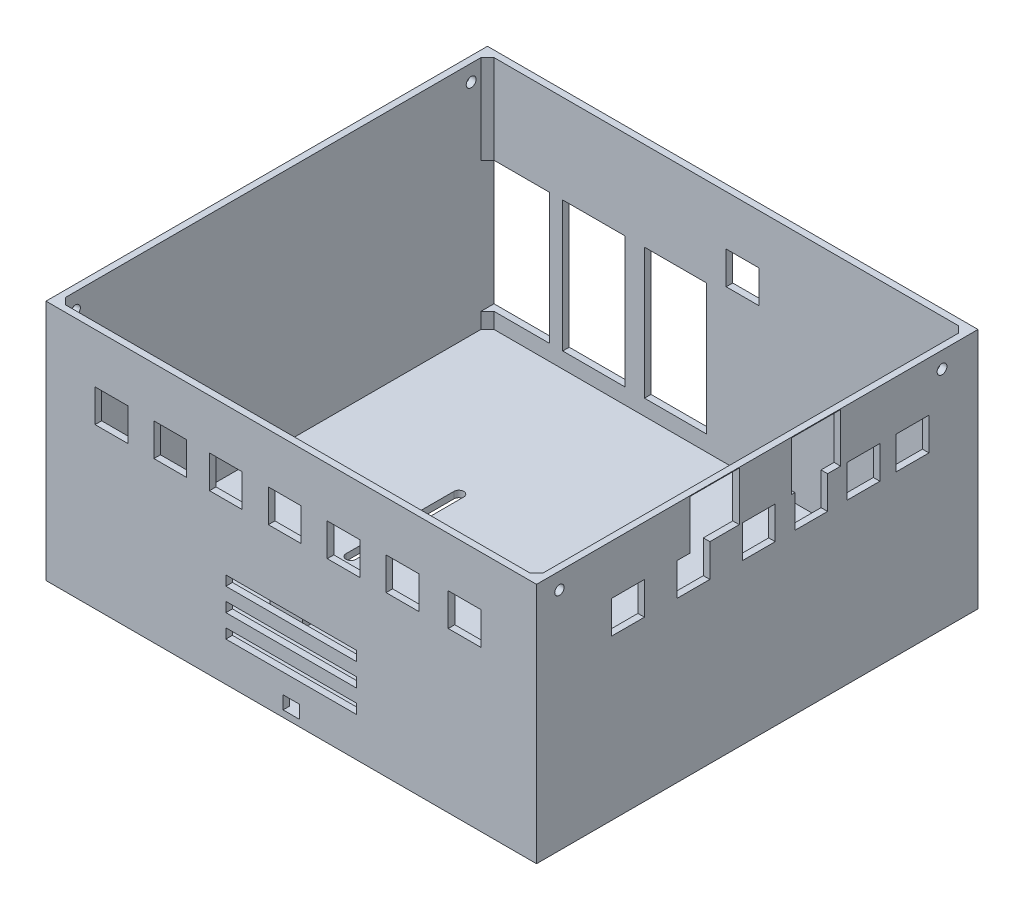
SolidWorks part; units mm, degrees
ref_plane "Alzado" through (0, 0, 0) normal (0, 0, 1) x (1, 0, 0)
ref_plane "Planta" through (0, 0, 0) normal (0, 1, 0) x (1, 0, 0)
ref_plane "Vista lateral" through (0, 0, 0) normal (1, 0, 0) x (0, 0, -1)
sketch "Croquis1" plane through (0, 0, 0) normal (0, 1, 0) x (1, 0, 0)
  line L1 (-75, -67.5) -> (75, -67.5)
  line L2 (-75, -67.5) -> (-75, 67.5)
  line L3 (-75, 67.5) -> (75, 67.5)
  line L4 (75, -67.5) -> (75, 67.5)
  line L5 (-75, -67.5) -> (75, 67.5) construction
  line L6 (-75, 67.5) -> (75, -67.5) construction
  point P0 (0, 0)
  dimension "D1" = 150
  dimension "D2" = 135
extrude "Saliente-Extruir1" add sketch "Croquis1" along normal blind 2
sketch "Croquis2" plane through (0, 2, 0) normal (0, 1, 0) x (1, 0, 0)
  line L0 (31.25, 16.5) -> (31.25, 1.5)
  line L1 (34.25, 1.5) -> (34.25, 16.5)
  line L2 (49.25, 1.5) -> (34.25, 1.5)
  line L3 (34.25, -1.5) -> (49.25, -1.5)
  line L4 (-75, -67.5) -> (75, -67.5) construction
  line L5 (75, -67.5) -> (75, 67.5) construction
  line L6 (-75, 67.5) -> (-75, -67.5) construction
  line L7 (75, 67.5) -> (-75, 67.5) construction
  line L8 (73, -65.5) -> (73, 65.5)
  line L9 (73, 65.5) -> (-73, 65.5)
  line L10 (-73, 65.5) -> (-73, -65.5)
  line L11 (-73, -65.5) -> (73, -65.5)
  line L12 (73, -65.5) -> (73, 65.5) construction
  line L13 (73, 65.5) -> (-73, 65.5) construction
  line L14 (-73, 65.5) -> (-73, -65.5) construction
  line L15 (-73, -65.5) -> (73, -65.5) construction
  line L16 (-75, -67.5) -> (75, -67.5)
  line L17 (75, -67.5) -> (75, 67.5)
  line L18 (-75, 67.5) -> (-75, -67.5)
  line L19 (75, 67.5) -> (-75, 67.5)
  line L21 (-73, 0) -> (73, 0) construction
  line L42 (-73, 65.5) -> (73, 65.5)
  line L43 (73, -65.5) -> (-73, -65.5)
  line L44 (34.25, -16.5) -> (34.25, -1.5)
  line L45 (31.25, -1.5) -> (31.25, -16.5)
  line L46 (16.25, -1.5) -> (31.25, -1.5)
  line L47 (31.25, 1.5) -> (16.25, 1.5)
  line L56 (-31.25, -16.5) -> (-31.25, -1.5)
  line L57 (-34.25, -1.5) -> (-34.25, -16.5)
  line L58 (-49.25, -1.5) -> (-34.25, -1.5)
  line L59 (-34.25, 1.5) -> (-49.25, 1.5)
  line L60 (-34.25, 16.5) -> (-34.25, 1.5)
  line L61 (-31.25, 1.5) -> (-31.25, 16.5)
  line L62 (-16.25, 1.5) -> (-31.25, 1.5)
  line L63 (-31.25, -1.5) -> (-16.25, -1.5)
  line L64 (0, 14.75) -> (0, -8.44) construction
  circle A8 centre (0, 0) radius 8.44
  arc A9 (31.25, 16.5) -> (34.25, 16.5) centre (32.75, 16.5) cw
  arc A10 (49.25, 1.5) -> (49.25, -1.5) centre (49.25, 0) cw
  arc A11 (16.25, 1.5) -> (16.25, -1.5) centre (16.25, 0) ccw
  circle A12 centre (0, 0) radius 8.44
  arc A13 (34.25, -16.5) -> (31.25, -16.5) centre (32.75, -16.5) cw
  circle A17 centre (0, 0) radius 8.44
  arc A19 (-31.25, -16.5) -> (-34.25, -16.5) centre (-32.75, -16.5) cw
  arc A20 (-49.25, -1.5) -> (-49.25, 1.5) centre (-49.25, 0) cw
  arc A21 (-16.25, -1.5) -> (-16.25, 1.5) centre (-16.25, 0) ccw
  circle A22 centre (0, 0) radius 8.44
  arc A23 (-34.25, 16.5) -> (-31.25, 16.5) centre (-32.75, 16.5) cw
  point P101 (0, 0)
  dimension "D1" = 2
  dimension "D13" = 4
extrude "Cortar-Extruir2" cut sketch "Croquis2" against normal blind 2 contours L60 L59 A20 L58 L57 A19 L56 L63 A21 L62 L61 A23 | L44 L3 A10 L2 L1 A9 L0 L47 A11 L46 L45 A13
sketch "Croquis4" plane through (0, 2, 0) normal (0, 1, 0) x (1, 0, 0)
  line L10 (-75, -67.5) -> (75, -67.5) construction
  line L11 (75, -67.5) -> (75, 67.5) construction
  line L12 (75, 67.5) -> (-75, 67.5) construction
  line L13 (-75, 67.5) -> (-75, -67.5) construction
  line L14 (-73, -65.5) -> (73, -65.5)
  line L15 (73, -65.5) -> (73, 65.5)
  line L16 (-73, 65.5) -> (-73, -65.5)
  line L17 (73, 65.5) -> (-73, 65.5)
  line L18 (-73, -65.5) -> (73, -65.5)
  line L19 (73, -65.5) -> (73, 65.5)
  line L20 (-73, 65.5) -> (-73, -65.5)
  line L21 (73, 65.5) -> (-73, 65.5)
  line L22 (-75, -67.5) -> (75, -67.5)
  line L23 (75, -67.5) -> (75, 67.5)
  line L24 (75, 67.5) -> (-75, 67.5)
  line L25 (-75, 67.5) -> (-75, -67.5)
  dimension "D1" = 2
extrude "Saliente-Extruir3" add sketch "Croquis4" along normal blind 72
sketch "Croquis5" plane through (-75, 0, 0) normal (-1, 0, 0) x (0, 0, 1)
  line L0 (-67.5, 74) -> (67.5, 74) construction
  line L1 (-65.5, 72) -> (-40.9426, 72) construction
  line L2 (-65.5, 72) -> (-65.5, 39.0856) construction
  line L5 (-67.5, 74) -> (-67.5, 0) construction
  circle A0 centre (-60.5, 69) radius 1.5
  dimension "D5" = 3
  dimension "D1" = 2
  dimension "D2" = 2
  dimension "D3" = 5
  dimension "D4" = 5
extrude "Cortar-Extruir3" cut sketch "Croquis5" against normal blind 2
sketch "Croquis6" plane through (-75, 0, 0) normal (-1, 0, 0) x (0, 0, 1)
  line L0 (42.5638, 72) -> (65.5, 72) construction
  line L1 (65.5, 72) -> (65.5, 36.9211) construction
  line L2 (-67.5, 74) -> (67.5, 74) construction
  line L3 (67.5, 74) -> (67.5, 0) construction
  circle A0 centre (60.5, 69) radius 1.5
  dimension "D3" = 3
  dimension "D1" = 2
  dimension "D2" = 2
  dimension "D4" = 5
  dimension "D5" = 5
extrude "Cortar-Extruir4" cut sketch "Croquis6" against normal blind 2
sketch "Croquis7" plane through (75, 0, 0) normal (1, 0, 0) x (0, 0, -1)
  line L0 (61.5, 43.6399) -> (61.5, 72) construction
  line L1 (61.5, 72) -> (54.1468, 72) construction
  line L2 (-67.5, 74) -> (67.5, 74) construction
  line L3 (67.5, 74) -> (67.5, 0) construction
  circle A0 centre (56.5, 69) radius 1.5
  dimension "D3" = 3
  dimension "D1" = 2
  dimension "D2" = 6
  dimension "D4" = 5
  dimension "D5" = 5
extrude "Cortar-Extruir5" cut sketch "Croquis7" against normal blind 2
sketch "Croquis8" plane through (75, 0, 0) normal (1, 0, 0) x (0, 0, -1)
  line L0 (-54.2689, 72) -> (-65.5, 72) construction
  line L1 (-65.5, 72) -> (-65.5, 42.9466) construction
  line L2 (-67.5, 74) -> (67.5, 74) construction
  line L3 (-67.5, 74) -> (-67.5, 0) construction
  circle A0 centre (-60.5, 69) radius 1.4318
  dimension "D1" = 2
  dimension "D2" = 2
  dimension "D3" = 3
  dimension "D4" = 5
extrude "Cortar-Extruir6" cut sketch "Croquis8" against normal blind 2
sketch "Croquis9" plane through (0, 0, 67.5) normal (0, 0, 1) x (1, 0, 0)
  line L0 (75, 58.8) -> (-75, 58.8) construction
  line L1 (75, 74) -> (75, 0) construction
  line L2 (-75, 74) -> (-75, 0) construction
  line L3 (-75, 74) -> (75, 74) construction
  line L4 (3, 48.8) -> (-7, 48.8)
  line L5 (-50, 58.8) -> (-60, 58.8)
  line L6 (-50, 58.8) -> (-50, 48.8)
  line L7 (-50, 48.8) -> (-60, 48.8)
  line L8 (-60, 58.8) -> (-60, 48.8)
  line L9 (-42, 58.8) -> (-32, 58.8)
  line L10 (-42, 58.8) -> (-42, 48.8)
  line L11 (-42, 48.8) -> (-32, 48.8)
  line L12 (-32, 58.8) -> (-32, 48.8)
  line L13 (-25, 58.8) -> (-15, 58.8)
  line L14 (-25, 58.8) -> (-25, 48.8)
  line L15 (-25, 48.8) -> (-15, 48.8)
  line L16 (-15, 58.8) -> (-15, 48.8)
  line L20 (3, 58.8) -> (3, 48.8)
  line L21 (11, 58.8) -> (21, 58.8)
  line L22 (11, 58.8) -> (11, 48.8)
  line L23 (11, 48.8) -> (21, 48.8)
  line L24 (21, 58.8) -> (21, 48.8)
  line L25 (29, 58.8) -> (39, 58.8)
  line L26 (29, 58.8) -> (29, 48.8)
  line L27 (29, 48.8) -> (39, 48.8)
  line L28 (39, 58.8) -> (39, 48.8)
  line L29 (48, 58.8) -> (58, 58.8)
  line L30 (48, 58.8) -> (48, 48.8)
  line L31 (48, 48.8) -> (58, 48.8)
  line L32 (58, 58.8) -> (58, 48.8)
  line L33 (-7, 48.8) -> (-7, 58.8)
  line L34 (-7, 58.8) -> (3, 58.8)
  dimension "D1" = 15.2
  dimension "D2" = 15
  dimension "D3" = 10
  dimension "D4" = 10
  dimension "D5" = 43
  dimension "D6" = 10
  dimension "D7" = 10
  dimension "D8" = 60
  dimension "D9" = 10
  dimension "D10" = 10
  dimension "D11" = 8
  dimension "D12" = 10
  dimension "D13" = 8
  dimension "D14" = 10
  dimension "D15" = 10
  dimension "D16" = 8
  dimension "D17" = 10
  dimension "D18" = 10
  dimension "D19" = 9
  dimension "D20" = 10
  dimension "D21" = 10
extrude "Cortar-Extruir7" cut sketch "Croquis9" against normal blind 2
sketch "Croquis10" plane through (75, 0, 0) normal (1, 0, 0) x (0, 0, -1)
  line L0 (67.5, 58.8) -> (-67.5, 58.8) construction
  line L1 (67.5, 74) -> (67.5, 0) construction
  line L2 (-67.5, 74) -> (-67.5, 0) construction
  line L3 (-67.5, 74) -> (67.5, 74) construction
  line L4 (11.5, 48.8) -> (11.5, 58.8)
  line L5 (-44.5, 58.8) -> (-34.5, 58.8)
  line L6 (-44.5, 58.8) -> (-44.5, 48.8)
  line L7 (-44.5, 48.8) -> (-34.5, 48.8)
  line L8 (-34.5, 58.8) -> (-34.5, 48.8)
  line L9 (-24.5, 58.8) -> (-14.5, 58.8)
  line L10 (-24.5, 58.8) -> (-24.5, 48.8)
  line L11 (-24.5, 48.8) -> (-14.5, 48.8)
  line L12 (-14.5, 58.8) -> (-14.5, 48.8)
  line L13 (-4.5, 58.8) -> (5.5, 58.8)
  line L14 (-4.5, 58.8) -> (-4.5, 48.8)
  line L15 (-4.5, 48.8) -> (5.5, 48.8)
  line L16 (5.5, 58.8) -> (5.5, 48.8)
  line L19 (11.5, 48.8) -> (21.5, 48.8)
  line L20 (21.5, 58.8) -> (21.5, 48.8)
  line L21 (27.5, 58.8) -> (37.5, 58.8)
  line L22 (27.5, 58.8) -> (27.5, 48.8)
  line L23 (27.5, 48.8) -> (37.5, 48.8)
  line L24 (37.5, 58.8) -> (37.5, 48.8)
  line L25 (42.5, 58.8) -> (52.5, 58.8)
  line L26 (42.5, 58.8) -> (42.5, 48.8)
  line L27 (42.5, 48.8) -> (52.5, 48.8)
  line L28 (52.5, 58.8) -> (52.5, 48.8)
  line L29 (21.5, 58.8) -> (11.5, 58.8)
  point P32 (32.5, 48.8)
  dimension "D1" = 15.2
  dimension "D2" = 10
  dimension "D3" = 10
  dimension "D4" = 10
  dimension "D5" = 10
  dimension "D6" = 10
  dimension "D7" = 10
  dimension "D8" = 10
  dimension "D9" = 10
  dimension "D10" = 10
  dimension "D11" = 10
  dimension "D12" = 10
  dimension "D13" = 10
  dimension "D14" = 23
  dimension "D15" = 53
  dimension "D16" = 73
  dimension "D17" = 6
  dimension "D18" = 15.2
  dimension "D19" = 15
  dimension "D20" = 6
extrude "Cortar-Extruir8" cut sketch "Croquis10" against normal blind 2
sketch "Croquis11" plane through (0, 0, -67.5) normal (0, 0, -1) x (-1, 0, 0)
  line L0 (75, 58.8) -> (-75, 58.8) construction
  line L1 (75, 74) -> (75, 0) construction
  line L2 (-75, 74) -> (-75, 0) construction
  line L3 (-75, 74) -> (75, 74) construction
  line L4 (-73, 58.8) -> (-73, 9.9054) construction
  line L6 (0, 48.8) -> (-10, 48.8)
  line L7 (0, 48.8) -> (0, 58.8)
  line L8 (0, 58.8) -> (-10, 58.8)
  line L9 (-10, 48.8) -> (-10, 58.8)
  line L10 (25, 6.8) -> (6, 6.8)
  line L11 (25, 6.8) -> (25, 46.8)
  line L12 (25, 46.8) -> (6, 46.8)
  line L13 (6, 6.8) -> (6, 46.8)
  line L15 (31, 6.8) -> (50, 6.8)
  line L16 (31, 6.8) -> (31, 46.8)
  line L17 (31, 46.8) -> (50, 46.8)
  line L18 (50, 6.8) -> (50, 46.8)
  line L19 (54, 6.8) -> (73, 6.8)
  line L20 (54, 6.8) -> (54, 46.8)
  line L21 (54, 46.8) -> (73, 46.8)
  line L22 (73, 6.8) -> (73, 46.8)
  dimension "D1" = 15.2
  dimension "D2" = 2
  dimension "D3" = 10
  dimension "D4" = 10
  dimension "D5" = 73
  dimension "D6" = 16
  dimension "D7" = 19
  dimension "D8" = 12
  dimension "D9" = 40
  dimension "D10" = 6
  dimension "D11" = 19
  dimension "D12" = 40
  dimension "D13" = 12
  dimension "D14" = 12
  dimension "D15" = 4
  dimension "D16" = 40
  dimension "D17" = 19
extrude "Cortar-Extruir9" cut sketch "Croquis11" against normal blind 2
sketch "Croquis12" plane through (75, 0, 0) normal (1, 0, 0) x (0, 0, -1)
  line L0 (25.5, 0) -> (25.5, 30.8414) construction
  line L1 (-67.5, 0) -> (67.5, 0) construction
  line L2 (67.5, 74) -> (67.5, 0) construction
  line L3 (10.5, 0) -> (10.5, 30.8414) construction
  line L5 (25.5, 58.8) -> (10.5, 58.8)
  line L6 (25.5, 58.8) -> (25.5, 73.8)
  line L7 (25.5, 73.8) -> (10.5, 73.8)
  line L8 (10.5, 58.8) -> (10.5, 73.8)
  line L9 (-20.5, 0) -> (-20.5, 33.6091) construction
  line L10 (-67.5, 74) -> (-67.5, 0) construction
  line L11 (-67.5, 74) -> (67.5, 74) construction
  line L12 (-20.5, 58.8) -> (-5.5, 58.8)
  line L13 (-20.5, 58.8) -> (-20.5, 73.8)
  line L14 (-20.5, 73.8) -> (-5.5, 73.8)
  line L15 (-5.5, 58.8) -> (-5.5, 73.8)
  dimension "D1" = 42
  dimension "D2" = 15
  dimension "D3" = 15
  dimension "D4" = 15.2
  dimension "D5" = 47
  dimension "D6" = 15.2
  dimension "D7" = 15
  dimension "D8" = 15
sketch "Croquis13" plane through (0, 0, 0) normal (0, -1, 0) x (1, 0, 0)
  line L0 (75, 55.5) -> (-75, 55.5) construction
  line L1 (75, 67.5) -> (75, -67.5) construction
  line L2 (-75, -67.5) -> (-75, 67.5) construction
  line L3 (-75, 67.5) -> (75, 67.5) construction
  line L4 (0, -67.5) -> (0, 67.5) construction
  line L5 (21.5, 55.5) -> (-21.5, 55.5) construction
  line L6 (21.5, 55.5) -> (21.5, 20.5) construction
  line L7 (21.5, 20.5) -> (-21.5, 20.5) construction
  line L8 (-21.5, 55.5) -> (-21.5, 20.5) construction
  line L9 (75, -67.5) -> (-75, -67.5) construction
  line L10 (21.5, 38) -> (-21.5, 38) construction
  line L11 (-21.5, 38) -> (-31.7475, 38) construction
  line L12 (21.5, 47) -> (-21.5, 47) construction
  line L13 (21.5, 47) -> (21.5, 29) construction
  line L14 (21.5, 29) -> (-21.5, 29) construction
  line L15 (-21.5, 47) -> (-21.5, 29) construction
  line L16 (21.5, 47) -> (-21.5, 29) construction
  line L17 (21.5, 29) -> (-21.5, 47) construction
  line L20 (-30.5, 38) -> (-21.5, 38)
  line L21 (30.5, 38) -> (21.5, 38)
  arc A2 (-21.5, 47) -> (-21.5, 29) centre (-21.5, 38) ccw construction
  circle A3 centre (-26, 38) radius 2
  circle A4 centre (26, 38) radius 2
  arc A5 (21.5, 47) -> (21.5, 29) centre (21.5, 38) cw construction
  point P18 (0, 38)
  point P24 (-26.6237, 38)
  dimension "D6" = 4
  dimension "D1" = 12
  dimension "D2" = 35
  dimension "D3" = 21.5
  dimension "D5" = 9
extrude "Cortar-Extruir11" cut sketch "Croquis13" against normal blind 2 contours A3 | A4
sketch "Croquis14" plane through (0, 2, 0) normal (0, 1, 0) x (1, 0, 0)
  line L1 (31, -33) -> (21, -33)
  line L2 (31, -33) -> (31, -43)
  line L3 (31, -43) -> (21, -43)
  line L4 (21, -33) -> (21, -43)
  line L5 (31, -33) -> (21, -43) construction
  line L6 (31, -43) -> (21, -33) construction
  line L7 (-21, -33) -> (-31, -33)
  line L8 (-21, -33) -> (-21, -43)
  line L9 (-21, -43) -> (-31, -43)
  line L10 (-31, -33) -> (-31, -43)
  line L11 (-21, -33) -> (-31, -43) construction
  line L12 (-21, -43) -> (-31, -33) construction
  circle A0 centre (-26, -38) radius 2 construction
  circle A1 centre (26, -38) radius 2 construction
  circle A2 centre (-26, -38) radius 2
  circle A3 centre (26, -38) radius 2
  point P0 (26, -38)
  point P6 (-26, -38)
  dimension "D1" = 10
  dimension "D2" = 10
  dimension "D3" = 10
  dimension "D4" = 10
extrude "Saliente-Extruir4" add sketch "Croquis14" along normal blind 5
sketch "Croquis15" plane through (0, 0, 67.5) normal (0, 0, 1) x (1, 0, 0)
  line L0 (0, 0) -> (0, 74) construction
  line L1 (-75, 0) -> (75, 0) construction
  line L2 (-75, 74) -> (75, 74) construction
  line L4 (2.5, 2) -> (-2.5, 2)
  line L5 (2.5, 2) -> (2.5, 6)
  line L6 (2.5, 6) -> (-2.5, 6)
  line L7 (-2.5, 2) -> (-2.5, 6)
  line L8 (20, 15) -> (-20, 15)
  line L9 (20, 15) -> (20, 12)
  line L10 (20, 12) -> (-20, 12)
  line L11 (-20, 15) -> (-20, 12)
  line L12 (-20, 22) -> (20, 22)
  line L13 (-20, 22) -> (-20, 19)
  line L14 (-20, 19) -> (20, 19)
  line L15 (20, 22) -> (20, 19)
  line L16 (-20, 29) -> (20, 29)
  line L17 (-20, 29) -> (-20, 26)
  line L18 (-20, 26) -> (20, 26)
  line L19 (20, 29) -> (20, 26)
  dimension "D1" = 2
  dimension "D2" = 4
  dimension "D3" = 2.5
  dimension "D4" = 5
  dimension "D5" = 20
  dimension "D6" = 40
  dimension "D7" = 3
  dimension "D8" = 10
  dimension "D9" = 4
  dimension "D10" = 4
  dimension "D11" = 20
  dimension "D12" = 20
  dimension "D13" = 40
  dimension "D14" = 40
  dimension "D15" = 3
  dimension "D16" = 3
extrude "Cortar-Extruir12" cut sketch "Croquis15" against normal blind 2
extrude "Cortar-Extruir13" cut sketch "Croquis12" against normal blind 2
sketch "Croquis16" plane through (0, 74, 0) normal (0, 1, 0) x (1, 0, 0)
  line L0 (-73, -65.5) -> (-73, -63.5)
  line L1 (-73, 65.5) -> (-73, -65.5) construction
  line L2 (-73, -63.5) -> (-71, -65.5)
  line L3 (-73, -65.5) -> (73, -65.5) construction
  line L4 (-71, -65.5) -> (-73, -65.5)
  line L5 (73, -65.5) -> (71, -65.5)
  line L6 (71, -65.5) -> (73, -63.5)
  line L7 (73, -63.5) -> (73, -65.5)
  line L8 (73, 65.5) -> (73, 63.5)
  line L9 (73, -65.5) -> (73, 65.5) construction
  line L10 (73, 63.5) -> (71, 65.5)
  line L11 (73, 65.5) -> (-73, 65.5) construction
  line L12 (71, 65.5) -> (73, 65.5)
  dimension "D1" = 2
  dimension "D2" = 2
  dimension "D3" = 2
  dimension "D4" = 2
  dimension "D5" = 2
  dimension "D6" = 2
extrude "Saliente-Extruir5" add sketch "Croquis16" along direction (0, -1, 0) on the side against the normal up to body (74 mm away) separate body
sketch "Croquis17" plane through (0, 74, 0) normal (0, 1, 0) x (1, 0, 0)
  line L0 (-73, 65.5) -> (-73, 63.5)
  line L1 (-73, 65.5) -> (-73, -63.5) construction
  line L2 (-73, 63.5) -> (-71, 65.5)
  line L3 (71, 65.5) -> (-73, 65.5) construction
  line L4 (-71, 65.5) -> (-73, 65.5)
  dimension "D1" = 2
  dimension "D2" = 2
extrude "Saliente-Extruir6" add sketch "Croquis17" against normal blind 27.2
sketch "Croquis18" plane through (0, 6.8, 0) normal (0, 1, 0) x (1, 0, 0)
  line L0 (-73, 65.5) -> (-71, 65.5)
  line L1 (-54, 65.5) -> (-73, 65.5) construction
  line L2 (-71, 65.5) -> (-73, 63.5)
  line L3 (-73, 63.5) -> (-73, 65.5)
  dimension "D1" = 2
  dimension "D2" = 2
extrude "Saliente-Extruir7" add sketch "Croquis18" against normal up to body separate body
